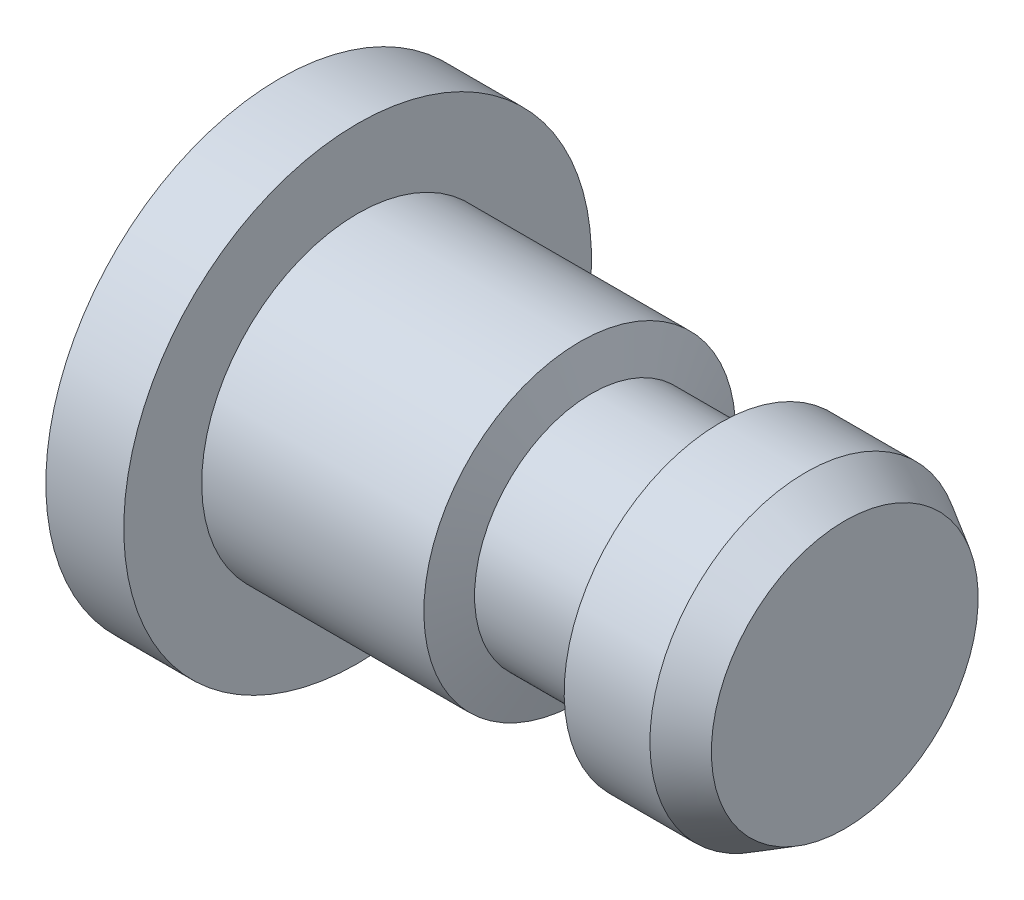
SolidWorks part; units mm, degrees
material "AISI 1045 Steel, cold drawn"
ref_plane "Front Plane" through (0, 0, 0) normal (0, 0, 1) x (1, 0, 0)
ref_plane "Top Plane" through (0, 0, 0) normal (0, 1, 0) x (1, 0, 0)
ref_plane "Right Plane" through (0, 0, 0) normal (1, 0, 0) x (0, 0, -1)
sketch "Sketch1" plane through (0, 0, 0) normal (0, 0, 1) x (1, 0, 0)
  line L0 (0, 0) -> (0, 6)
  line L1 (0, 6) -> (2, 6)
  line L2 (2, 6) -> (2, 4)
  line L3 (2, 4) -> (7.7, 4)
  line L4 (7.7, 4) -> (8, 3)
  line L5 (8, 3) -> (11, 3)
  line L6 (11, 3) -> (11.3, 4)
  line L7 (11.3, 4) -> (14.5, 4)
  line L8 (14.5, 4) -> (14.5, 0)
  line L9 (14.5, 0) -> (0, 0)
  dimension "D1" = 6
  dimension "D2" = 4
  dimension "D3" = 5.7
  dimension "D4" = 1
  dimension "D5" = 3
  dimension "D6" = 3.6
  dimension "D7" = 12.5
  dimension "D8" = 14.5
revolve "Revolve1" add sketch "Sketch1" angle 360 about L9
chamfer "Chamfer1" distance 1 angle 30 1 edges at (14.5, 4, 0)
